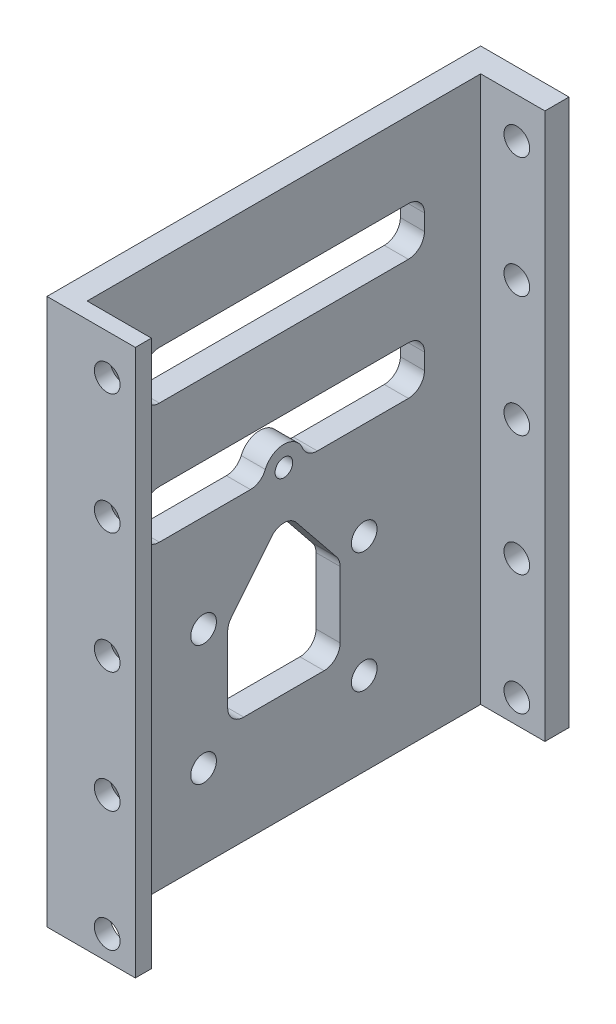
SolidWorks part; units mm, degrees
material "PET"
ref_plane "前视基准面" through (0, 0, 0) normal (0, 0, 1) x (1, 0, 0)
ref_plane "上视基准面" through (0, 0, 0) normal (0, 1, 0) x (1, 0, 0)
ref_plane "右视基准面" through (0, 0, 0) normal (1, 0, 0) x (0, 0, -1)
other "Configuration Table"
sketch "草图1" plane through (0, 0, 0) normal (0, 1, 0) x (1, 0, 0)
  line L0 (0, 0) -> (8, 0)
  line L1 (8, 0) -> (8, -3)
  line L2 (8, -3) -> (-3, -3)
  line L3 (-3, -3) -> (-3, 49)
  line L4 (-3, 49) -> (0, 49)
  line L5 (0, 49) -> (0, 0)
  dimension "D1" = 3
  dimension "D2" = 3
  dimension "D3" = 52
  dimension "D4" = 8
extrude "凸台-拉伸1" add sketch "草图1" along normal blind 120
sketch "草图2" plane through (0, 0, 0) normal (0, 0, -1) x (-1, 0, 0)
  line L0 (-8, 60) -> (-4.5, 60) construction
  line L1 (-8, 120) -> (-8, 0) construction
  line L2 (-4.5, 60) -> (-4.5, 45) construction
  line L3 (-8, 60) -> (3, 60) construction
  line L4 (3, 120) -> (3, 0) construction
  line L5 (0, 120) -> (0, 0) construction
  circle A0 centre (-4.5, 60) radius 1.6
  circle A1 centre (-4.5, 45) radius 1.6
  circle A2 centre (-4.5, 30) radius 1.6
  circle A3 centre (-4.5, 15) radius 1.6
  circle A4 centre (-4.5, 75) radius 1.6
  circle A5 centre (-4.5, 90) radius 1.6
  circle A6 centre (-4.5, 105) radius 1.6
  dimension "D2" = 3.2
  dimension "D1" = 4.5
  dimension "D4" = 15
  dimension "D3" = 4
extrude "切除-拉伸1" cut sketch "草图2" against normal blind 120
sketch "草图3" plane through (0, 0, 0) normal (1, 0, 0) x (0, 0, -1)
  line L0 (0, 120) -> (49, 120) construction
  line L1 (24.5, 120) -> (24.5, 0) construction
  line L2 (0, 0) -> (49, 0) construction
  line L3 (24.5, 7.3845) -> (14.5, 7.3845) construction
  circle A0 centre (14.5, 7.3845) radius 1.6
  circle A1 centre (14.5, 22.3845) radius 1.6
  circle A2 centre (14.5, 37.3845) radius 1.6
  circle A3 centre (14.5, 52.3845) radius 1.6
  circle A4 centre (14.5, 67.3845) radius 1.6
  circle A5 centre (34.5, 67.3845) radius 1.6
  circle A6 centre (34.5, 52.3845) radius 1.6
  circle A7 centre (34.5, 37.3845) radius 1.6
  circle A8 centre (34.5, 22.3845) radius 1.6
  circle A9 centre (34.5, 7.3845) radius 1.6
  dimension "D2" = 3.2
  dimension "D1" = 10
  dimension "D3" = 5
extrude "切除-拉伸2" cut sketch "草图3" against normal blind 10
sketch "草图4" plane through (0, 0, 0) normal (1, 0, 0) x (0, 0, -1)
  line L0 (0, 120) -> (49, 120) construction
  line L1 (24.5, 120) -> (24.5, 0) construction
  line L2 (0, 0) -> (49, 0) construction
  line L3 (24.5, 117) -> (15.7, 117) construction
  circle A0 centre (15.7, 117) radius 1.1
  circle A1 centre (33.3, 117) radius 1.1
  circle A2 centre (24.5, 79.8) radius 1.1
  dimension "D2" = 2.2
  dimension "D3" = 37.2
  dimension "D4" = 2.2
  dimension "D1" = 8.8
  dimension "D5" = 3
extrude "切除-拉伸3" cut sketch "草图4" against normal blind 12
ref_plane "基准面1" through (0, 0, -24.5) normal (0, 0, -1) x (-1, 0, 0)
sketch "草图5" plane through (0, 0, -49) normal (0, 0, -1) x (-1, 0, 0)
  line L1 (3, 120) -> (-8, 120)
  line L2 (3, 120) -> (3, 0)
  line L3 (3, 0) -> (-8, 0)
  line L4 (-8, 120) -> (-8, 0)
extrude "凸台-拉伸2" add sketch "草图5" along normal blind 2
mirror "镜向3" about plane through (0, 0, -24.5) normal (0, 0, -1) of "切除-拉伸1"
sketch "草图6" plane through (0, 0, 0) normal (1, 0, 0) x (0, 0, -1)
  line L0 (0, 0) -> (0, 30)
  line L1 (0, 120) -> (0, 0) construction
  line L2 (0, 30) -> (49, 30)
  line L3 (49, 120) -> (49, 0) construction
  line L4 (49, 30) -> (49, 0)
  line L5 (49, 0) -> (0, 0)
  dimension "D1" = 30
extrude "切除-拉伸4" cut sketch "草图6" against normal blind 10
sketch "草图7" plane through (0, 0, 0) normal (1, 0, 0) x (0, 0, -1)
  line L0 (0, 30) -> (-3, 30)
  line L1 (-3, 120) -> (-3, 0) construction
  line L2 (-3, 30) -> (-3, 0)
  line L3 (-3, 0) -> (0, 0)
  line L4 (0, 0) -> (0, 30)
extrude "切除-拉伸5" cut sketch "草图7" against normal blind 16 and the other way blind 42
sketch "草图8" plane through (0, 0, 0) normal (1, 0, 0) x (0, 0, -1)
  line L0 (49, 120) -> (49, 30) construction
  line L1 (-3, 30) -> (49, 30)
  line L2 (-3, 30) -> (-3, 42)
  line L3 (-3, 42) -> (49, 42)
  line L4 (49, 30) -> (49, 42)
  dimension "D1" = 12
extrude "切除-拉伸6" cut sketch "草图8" against normal blind 11 and the other way blind 35
sketch "草图9" plane through (-3, 0, 0) normal (-1, 0, 0) x (0, 0, 1)
  line L1 (-51, 0) -> (-49, 0)
  line L2 (-51, 0) -> (-51, 42)
  line L3 (-51, 42) -> (-49, 42)
  line L4 (-49, 0) -> (-49, 42)
extrude "切除-拉伸7" cut sketch "草图9" against normal blind 20
sketch "草图10" plane through (0, 120, 0) normal (0, 1, 0) x (1, 0, 0)
  line L1 (-3, 51) -> (8, 51)
  line L2 (-3, 51) -> (-3, -3)
  line L3 (-3, -3) -> (8, -3)
  line L4 (8, 51) -> (8, -3)
extrude "切除-拉伸8" cut sketch "草图10" against normal blind 10
sketch "草图11" plane through (0, 0, -51) normal (0, 0, -1) x (-1, 0, 0)
  line L4 (3, 110) -> (-8, 110)
  line L5 (-8, 110) -> (-8, 42)
  line L6 (-8, 42) -> (3, 42)
  line L7 (3, 42) -> (3, 110)
  line L8 (3, 110) -> (-8, 110)
  line L9 (-8, 110) -> (-8, 42)
  line L10 (-8, 42) -> (3, 42)
  line L11 (3, 42) -> (3, 110)
  circle A0 centre (-4.5, 105) radius 1.6 construction
  circle A1 centre (-4.5, 105) radius 1.6
  circle A2 centre (-4.5, 45) radius 1.6 construction
  circle A3 centre (-4.5, 60) radius 1.6 construction
  circle A4 centre (-4.5, 75) radius 1.6 construction
  circle A5 centre (-4.5, 90) radius 1.6 construction
  circle A6 centre (-4.5, 45) radius 1.6
  circle A7 centre (-4.5, 60) radius 1.6
  circle A8 centre (-4.5, 75) radius 1.6
  circle A9 centre (-4.5, 90) radius 1.6
  dimension "D1" = 0
extrude "凸台-拉伸3" add sketch "草图11" along normal blind 1
sketch "草图12" plane through (0, 110, 0) normal (0, 1, 0) x (1, 0, 0)
  line L0 (8, -3) -> (8, 0) construction
  line L1 (-3, -3) -> (8, -3)
  line L2 (-3, -3) -> (-3, -2)
  line L3 (-3, -2) -> (8, -2)
  line L4 (8, -3) -> (8, -2)
  dimension "D1" = 1
extrude "切除-拉伸9" cut sketch "草图12" against normal blind 91
sketch "草图13" plane through (-3, 0, 0) normal (-1, 0, 0) x (0, 0, 1)
  line L0 (-34.5, 67.3845) -> (-24.5, 79.8) construction
  line L1 (-24.5, 79.8) -> (-14.5, 67.3845) construction
  line L2 (-14.5, 67.3845) -> (-14.5, 52.3845) construction
  line L3 (-14.5, 52.3845) -> (-34.5, 52.3845) construction
  line L4 (-34.5, 52.3845) -> (-34.5, 67.3845) construction
  line L5 (-31.5, 66.3265) -> (-24.5, 75.0174)
  line L6 (-24.5, 75.0174) -> (-17.5, 66.3265)
  line L7 (-17.5, 66.3265) -> (-17.5, 55.3845)
  line L8 (-17.5, 55.3845) -> (-31.5, 55.3845)
  line L9 (-31.5, 55.3845) -> (-31.5, 66.3265)
  dimension "D1" = 3
extrude "切除-拉伸10" cut sketch "草图13" against normal blind 10
sketch "草图14" plane through (-3, 0, 0) normal (-1, 0, 0) x (0, 0, 1)
  line L0 (-49, 103.4) -> (-49, 91.6) construction
  line L1 (-49, 97.5) -> (0, 97.5) construction
  line L2 (0, 110) -> (0, 42) construction
  line L3 (-49, 88.4) -> (-49, 76.6) construction
  line L4 (-42, 94.5) -> (-7, 94.5)
  line L5 (-42, 94.5) -> (-42, 100.5)
  line L6 (-42, 100.5) -> (-7, 100.5)
  line L7 (-7, 94.5) -> (-7, 100.5)
  line L8 (-42, 94.5) -> (-7, 100.5) construction
  line L9 (-42, 100.5) -> (-7, 94.5) construction
  line L10 (-49, 82.5) -> (0, 82.5) construction
  line L11 (-22.0181, 79.5) -> (-7, 79.5)
  line L12 (-42, 79.5) -> (-26.9819, 79.5)
  line L13 (-42, 79.5) -> (-42, 85.5)
  line L14 (-42, 85.5) -> (-7, 85.5)
  line L15 (-7, 79.5) -> (-7, 85.5)
  line L16 (-42, 79.5) -> (-7, 85.5) construction
  line L17 (-42, 85.5) -> (-7, 79.5) construction
  arc A0 (-22.0181, 79.5) -> (-26.9819, 79.5) centre (-24.5, 79.8) ccw
  point P8 (-24.5, 97.5)
  point P19 (-24.5, 82.5)
  dimension "D4" = 5
  dimension "D1" = 35
  dimension "D2" = 6
  dimension "D3" = 6
extrude "切除-拉伸11" cut sketch "草图14" against normal blind 10
fillet "圆角1" radius 2 15 edges at (-1.5, 94.5, -7) (-1.5, 100.5, -7) (-1.5, 100.5, -42) (-1.5, 94.5, -42) (-1.5, 79.5, -42) (-1.5, 85.5, -42) (-1.5, 85.5, -7) (-1.5, 79.5, -7) (-1.5, 79.5, -22.0181) (-1.5, 79.5, -26.9819) (-1.5, 66.3265, -17.5) (-1.5, 55.3845, -17.5) (-1.5, 55.3845, -31.5) (-1.5, 66.3265, -31.5) (-1.5, 75.0174, -24.5)
